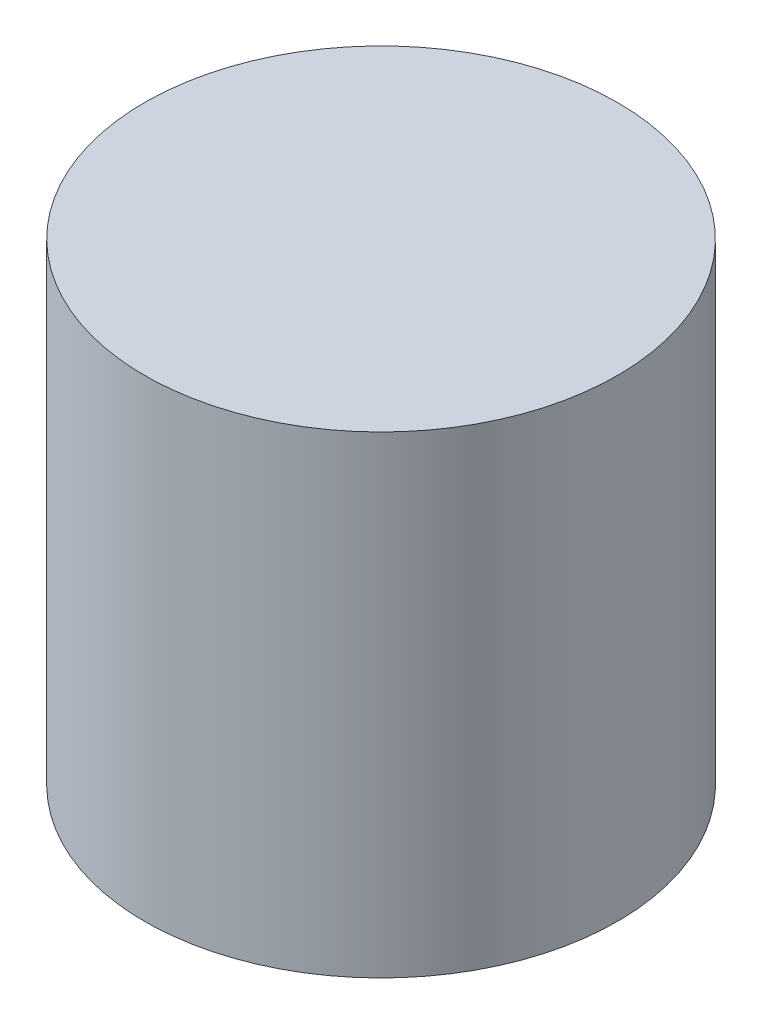
SolidWorks part; units mm, degrees
ref_plane "Front Plane" through (0, 0, 0) normal (0, 0, 1) x (1, 0, 0)
ref_plane "Top Plane" through (0, 0, 0) normal (0, 1, 0) x (1, 0, 0)
ref_plane "Right Plane" through (0, 0, 0) normal (1, 0, 0) x (0, 0, -1)
sketch "Sketch1" plane through (0, 0, 0) normal (0, 0, 1) x (1, 0, 0)
  line L1 (0, 0) -> (35, 0)
  line L2 (0, 0) -> (0, 70)
  line L3 (0, 70) -> (35, 70)
  line L4 (35, 0) -> (35, 70)
  dimension "D1" = 35
  dimension "D2" = 70
revolve "Revolve1" add sketch "Sketch1" angle 360 about L2
sketch3d "3DSketch2"
  line L0 (-32.6917, 0, -12.5) -> (-32.6917, 70, -12.5) construction
  line L1 (-32.6917, 65, 12.5) -> (-32.6917, 65, -12.5)
  line L2 (-32.6917, 65, 12.5) -> (-32.6917, 5, 12.5)
  line L3 (-32.6917, 5, 12.5) -> (-32.6917, 5, -12.5)
  line L4 (-32.6917, 65, -12.5) -> (-32.6917, 5, -12.5)
  line L5 (-34.9552, 70, -1.7698) -> (-65.3315, 70, -1.7698) construction
  circle A0 centre (0, 0, 0) radius 35 construction
  circle A1 centre (0, 70, 0) radius 35 construction
  point P4 (-32.6917, 35, -12.5)
  point P7 (-32.6917, 35, -12.5)
  point P14 (0, -35, 0)
  point P17 (0, 35, 0)
  dimension "D1" = 60
  dimension "D2" = 25
extrude "Cut-Extrude17" cut sketch "3DSketch2" along direction (-1, 0, 0) on the side against the normal blind 2.5 contours L1 L4 L3 L2
sketch "Sketch2" plane through (0, 0, 0) normal (0, -1, 0) x (1, 0, 0)
  line L0 (0, 0) -> (-47.5212, 0) construction
  line L1 (0, 0) -> (0, -55.4061) construction
sketch3d "3DSketch3"
  line L1 (0, 0, 0) -> (0, 0, -55.4061) construction
  line L3 (-18.6666, 54.9863, -29.6067) -> (17.3852, 54.9863, -30.3769)
  line L4 (-18.6666, 54.9863, -29.6067) -> (-18.6666, 14.9863, -29.6067)
  line L5 (-18.6666, 14.9863, -29.6067) -> (17.3852, 14.9863, -30.3769)
  line L6 (17.3852, 54.9863, -30.3769) -> (17.3852, 14.9863, -30.3769)
  line L7 (-18.6666, 54.9863, -29.6067) -> (17.3852, 14.9863, -30.3769) construction
  line L8 (-18.6666, 14.9863, -29.6067) -> (17.3852, 54.9863, -30.3769) construction
  point P0 (-0.6407, 14.9863, -29.9918)
  point P3 (103.828, -130.2601, 0)
  point P8 (0, 0, 0)
  point P9 (-0.6407, 34.9863, -29.9918)
  point P13 (0, 0, 0)
  point P14 (0, 0, 0)
  point P15 (0, 0, 0)
  point P16 (0, 0, 0)
  point P17 (0, 0, 0)
  point P18 (24.1833, -97.9712, 0)
  point P19 (0, 0, 0)
  point P20 (0, 0, 0)
  point P21 (6.7067, -101.7217, 0)
  point P22 (0, 0, 0)
  point P23 (30.6285, -105.6424, 0)
  point P24 (0, 0, 0)
  point P25 (0, 0, 0)
  point P26 (23.4989, -108.5882, 0)
  point P27 (7.0149, -114.6149, 0)
  point P28 (0, 0, 0)
  point P29 (0, 0, 0)
  dimension "D1" = 40
  dimension "D2" = 36.06
  dimension "D3" = 15
extrude "Cut-Extrude25" cut sketch "3DSketch3" along direction (0, 0, -1) on the side against the normal blind 116 contours L4 L5 L6 L3
